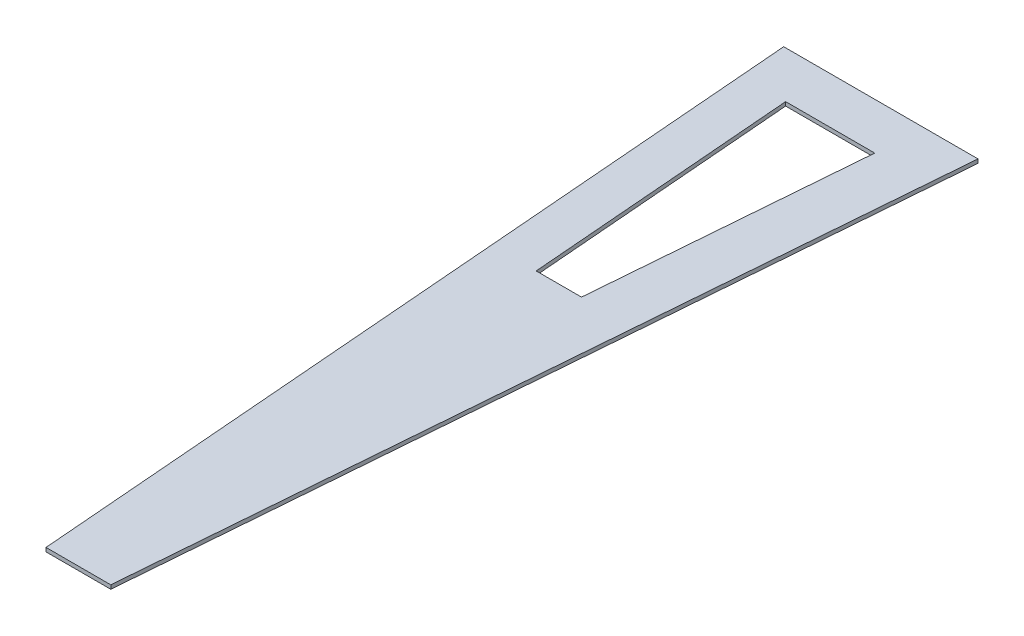
SolidWorks part; units mm, degrees
material "Balsa"
ref_plane "Front Plane" through (0, 0, 0) normal (0, 0, 1) x (1, 0, 0)
ref_plane "Top Plane" through (0, 0, 0) normal (0, 1, 0) x (1, 0, 0)
ref_plane "Right Plane" through (0, 0, 0) normal (1, 0, 0) x (0, 0, -1)
sketch "Sketch1" plane through (0, 0, 0) normal (0, 1, 0) x (1, 0, 0)
  line L0 (0, 0) -> (76.2, 0)
  line L1 (76.2, 0) -> (50.8, -314.706)
  line L2 (50.8, -314.706) -> (25.4, -314.706)
  line L3 (25.4, -314.706) -> (0, 0)
  dimension "D1" = 76.2
  dimension "D2" = 25.4
  dimension "D3" = 314.706
extrude "Boss-Extrude1" add sketch "Sketch1" along normal blind 1.524
sketch "Sketch4" plane through (0, 0, 0) normal (0, -1, 0) x (-1, 0, 0)
  line L3 (-27.6126, -124.6896) -> (-45.3926, -124.6896)
  line L4 (-45.3926, -124.6896) -> (-53.982, -18.2672)
  line L5 (-53.982, -18.2672) -> (-19.0233, -18.2672)
  line L6 (-19.0233, -18.2672) -> (-27.6126, -124.6896)
  line L7 (0, 0) -> (-25.4, -314.706) construction
  line L8 (-50.8, -314.706) -> (-76.2, 0) construction
  dimension "D2" = 34.9587
extrude "Cut-Extrude1" cut sketch "Sketch4" against normal blind 1.524
